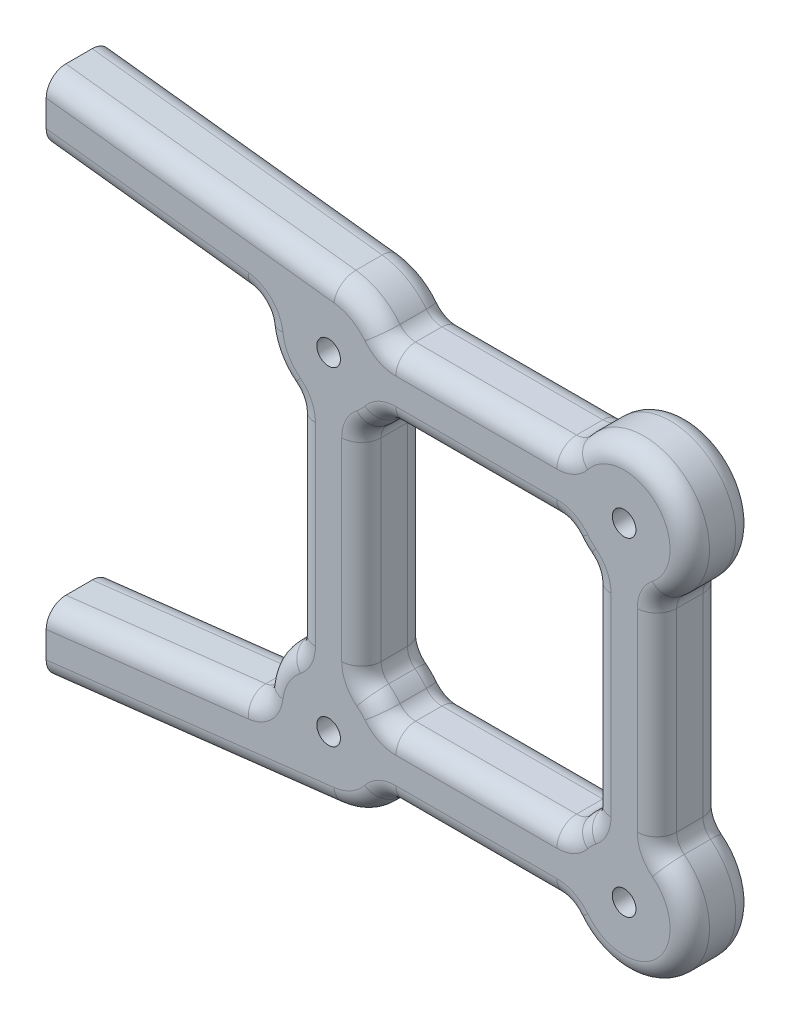
SolidWorks part; units mm, degrees
ref_plane "Front Plane" through (0, 0, 0) normal (1, 0, 0) x (0, 1, 0)
ref_plane "Top Plane" through (0, 0, 0) normal (0, 0, 1) x (0, 1, 0)
ref_plane "Right Plane" through (0, 0, 0) normal (0, 1, 0) x (-1, 0, 0)
sketch "Sketch1" plane through (0, 0, 0) normal (0, 0, 1) x (0, 1, 0)
  line L1 (-25, 22.5) -> (25, 22.5) construction
  line L2 (-25, 22.5) -> (-25, -22.5) construction
  line L3 (-25, -22.5) -> (25, -22.5) construction
  line L4 (25, 22.5) -> (25, -22.5) construction
  line L5 (-25, 22.5) -> (25, -22.5) construction
  line L6 (-25, -22.5) -> (25, 22.5) construction
  line L7 (-16.3397, 17.5) -> (16.3397, 17.5)
  line L9 (-16.3397, 27.5) -> (16.3397, 27.5)
  line L11 (-16.3397, 17.5) -> (16.3397, 27.5) construction
  line L12 (-16.3397, 27.5) -> (16.3397, 17.5) construction
  line L13 (-16.3397, -27.5) -> (16.3397, -27.5)
  line L15 (-16.3397, -17.5) -> (16.3397, -17.5)
  line L17 (-16.3397, -27.5) -> (16.3397, -17.5) construction
  line L18 (-16.3397, -17.5) -> (16.3397, -27.5) construction
  line L20 (-30, -13.8397) -> (-30, 13.8397)
  line L22 (-20, -13.8397) -> (-20, 13.8397)
  line L23 (-30, -13.8397) -> (-20, 13.8397) construction
  line L24 (-30, 13.8397) -> (-20, -13.8397) construction
  line L26 (20, -13.8397) -> (20, 13.8397)
  line L28 (30, -13.8397) -> (30, 13.8397)
  line L29 (20, -13.8397) -> (30, 13.8397) construction
  line L30 (20, 13.8397) -> (30, -13.8397) construction
  line L31 (-26.155, 32.4331) -> (-30, 65.5)
  line L32 (-34.9331, 21.345) -> (-40.0674, 65.5)
  line L33 (-30, 65.5) -> (-40.0674, 65.5)
  line L34 (26.155, 32.4331) -> (30, 65.5)
  line L35 (30, 65.5) -> (40.0674, 65.5)
  line L36 (40.0674, 65.5) -> (34.9331, 21.345)
  line L37 (-30, 65.5) -> (30, 65.5) construction
  arc A0 (-16.3397, 27.5) -> (-26.155, 32.4331) centre (-25, 22.5) ccw
  arc A1 (30, 13.8397) -> (34.9331, 21.345) centre (25, 22.5) ccw
  arc A2 (16.3397, -27.5) -> (30, -13.8397) centre (25, -22.5) ccw
  arc A3 (-16.3397, -17.5) -> (-20, -13.8397) centre (-25, -22.5) ccw
  arc A4 (20, -13.8397) -> (16.3397, -17.5) centre (25, -22.5) ccw
  arc A5 (16.3397, 17.5) -> (20, 13.8397) centre (25, 22.5) ccw
  arc A6 (-20, 13.8397) -> (-16.3397, 17.5) centre (-25, 22.5) ccw
  arc A7 (-30, -13.8397) -> (-16.3397, -27.5) centre (-25, -22.5) ccw
  arc A8 (-34.9331, 21.345) -> (-30, 13.8397) centre (-25, 22.5) ccw
  arc A9 (26.155, 32.4331) -> (16.3397, 27.5) centre (25, 22.5) ccw
  point P0 (0, 0)
  point P6 (0, 65.5)
  point P10 (0, 22.5)
  point P15 (0, -22.5)
  point P20 (-25, 0)
  point P25 (25, 0)
  dimension "D1" = 20
  dimension "D2" = 50
  dimension "D3" = 45
  dimension "D4" = 10
  dimension "D5" = 10
  dimension "D6" = 60
  dimension "D7" = 10
extrude "Boss-Extrude1" add sketch "Sketch1" along normal blind 10
fillet "Fillet1" radius 3 18 edges at (-17.5, 16.3397, 5) (-13.8397, 20, 5) (13.8397, 20, 5) (17.5, 16.3397, 5) (17.5, -16.3397, 5) (13.8397, -20, 5) (-17.5, -16.3397, 5) (-13.8397, -20, 5) (-13.8397, 30, 5) (13.8397, 30, 5) (-32.4331, 26.155, 5) (-27.5, 16.3397, 5) (-27.5, -16.3397, 5) (-32.4331, -26.155, 5) (-13.8397, -30, 5) (13.8397, -30, 5) (27.5, -16.3397, 5) (27.5, 16.3397, 5)
fillet "Fillet2" radius 3 80 edges at (-50.2822, 28.2305, 10) (-33.2911, 25.6038, 10) (-31.2151, 20.0963, 10) (-27.8038, 16.0686, 10) (-50.2822, -28.2305, 10) (-33.2911, -25.6038, 10) (-31.2151, -20.0963, 10) (-27.8038, -16.0686, 10) (-50.2822, 28.2305, 0) (-33.2911, 25.6038, 0) (-31.2151, 20.0963, 0) (-27.8038, 16.0686, 0) (-50.2822, -28.2305, 0) (-33.2911, -25.6038, 0) (-31.2151, -20.0963, 0) (-27.8038, -16.0686, 0) (17.1962, -16.0686, 0) (15.4289, -17.9289, 0) (13.5686, -19.6962, 0) (0, -20, 0) (-13.5686, -19.6962, 0) (-15.4289, -17.9289, 0) (-17.1962, -16.0686, 0) (-17.5, 0, 0) (-17.1962, 16.0686, 0) (-15.4289, 17.9289, 0) (-13.5686, 19.6962, 0) (0, 20, 0) (13.5686, 19.6962, 0) (15.4289, 17.9289, 0) (17.1962, 16.0686, 0) (-43.4225, -37.5002, 10) (-17.6022, -33.7184, 10) (-13.5686, -30.3038, 10) (0, -30, 10) (13.5686, -30.3038, 10) (29.5711, -32.0711, 10) (27.8038, -16.0686, 10) (-43.4225, 37.5002, 10) (-17.6022, 33.7184, 10) (-13.5686, 30.3038, 10) (0, 30, 10) (13.5686, 30.3038, 10) (29.5711, 32.0711, 10) (27.8038, 16.0686, 10) (17.1962, -16.0686, 10) (15.4289, -17.9289, 10) (13.5686, -19.6962, 10) (0, -20, 10) (-13.5686, -19.6962, 10) (-15.4289, -17.9289, 10) (-17.1962, -16.0686, 10) (-17.5, 0, 10) (-17.1962, 16.0686, 10) (-15.4289, 17.9289, 10) (-13.5686, 19.6962, 10) (0, 20, 10) (13.5686, 19.6962, 10) (15.4289, 17.9289, 10) (17.1962, 16.0686, 10) (-27.5, 0, 10) (-27.5, 0, 0) (17.5, 0, 0) (27.5, 0, 10) (17.5, 0, 10) (-43.4225, -37.5002, 0) (-17.6022, -33.7184, 0) (-13.5686, -30.3038, 0) (0, -30, 0) (13.5686, -30.3038, 0) (29.5711, -32.0711, 0) (27.8038, -16.0686, 0) (-43.4225, 37.5002, 0) (-17.6022, 33.7184, 0) (-13.5686, 30.3038, 0) (0, 30, 0) (13.5686, 30.3038, 0) (29.5711, 32.0711, 0) (27.8038, 16.0686, 0) (27.5, 0, 0)
sketch "Sketch2" plane through (-65.5, 0, 0) normal (-1, 0, 0) x (0, -1, 0)
  line L0 (-40.0674, 5) -> (-34.0674, 5) construction
  line L3 (40.0674, 5) -> (34.0674, 5) construction
  line L6 (-40.0674, 7) -> (-40.0674, 3) construction
  line L7 (40.0674, 7) -> (40.0674, 3) construction
  circle A0 centre (-34.0674, 5) radius 2.075
  circle A1 centre (34.0674, 5) radius 2.075
  dimension "D1" = 4.15
  dimension "D2" = 6
  dimension "D3" = 6
extrude "Cut-Extrude1" cut sketch "Sketch2" against normal blind 7 contours A1 | A0
sketch "Sketch3" plane through (0, 0, 0) normal (0, 0, -1) x (1, 0, 0)
  point P0 (22.5, 25)
  point P1 (22.5, -25)
  point P3 (-22.5, -25)
  point P5 (-22.5, 25)
hole_wizard "CBORE for M3 SHCS1" positions "Sketch3" profile "Sketch4" counterbore size "M3" standard "ANSI Metric" end condition up to next
sketch "Sketch4" plane through (22.5, -25, 0) normal (1, 0, 0) x (0, 1, 0)
  line L0 (0, 0) -> (0, 10)
  line L1 (0, 10) -> (1.8, 10)
  line L3 (1.8, 10) -> (1.8, 3)
  line L4 (1.8, 3) -> (3.25, 3)
  line L5 (3.25, 3) -> (3.25, 0)
  line L7 (3.25, 0) -> (0, 0)
  line L11 (0, -6.35) -> (0, 107.95) construction
  dimension "Thru Hole Dia." = 3.6
  dimension "Thru Hole Depth" = 10
  dimension "C'Bore Dia." = 6.5
  dimension "C'Bore Depth" = 3
